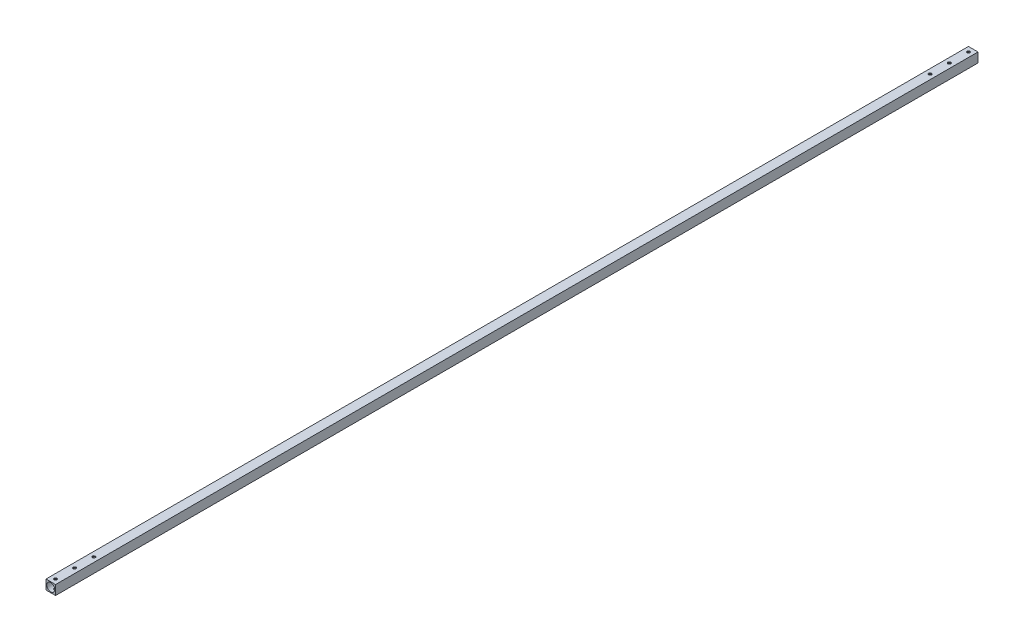
SolidWorks part; units mm, degrees
material "Thornel VCB-20 Carbon Cloth"
ref_plane "Front Plane" through (0, 0, 0) normal (0, 0, 1) x (1, 0, 0)
ref_plane "Top Plane" through (0, 0, 0) normal (0, 1, 0) x (1, 0, 0)
ref_plane "Right Plane" through (0, 0, 0) normal (1, 0, 0) x (0, 0, -1)
sketch "Sketch1" plane through (0, 0, 0) normal (0, 0, 1) x (1, 0, 0)
  line L1 (-5, -5) -> (5, -5)
  line L2 (-5, -5) -> (-5, 5)
  line L3 (-5, 5) -> (5, 5)
  line L4 (5, -5) -> (5, 5)
  line L5 (-5, -5) -> (5, 5) construction
  line L6 (-5, 5) -> (5, -5) construction
  circle A0 centre (0, 0) radius 4.25
  point P0 (0, 0)
  dimension "D3" = 8.5
  dimension "D1" = 10
  dimension "D2" = 10
extrude "Boss-Extrude1" add sketch "Sketch1" along normal blind 964
sketch "Sketch2" plane through (0, 5, 0) normal (0, 1, 0) x (1, 0, 0)
  line L0 (0, 0) -> (0, -5) construction
  line L1 (0, -5) -> (0, -25) construction
  line L2 (0, -25) -> (0, -45) construction
  line L3 (0, -964) -> (0, -959) construction
  line L4 (5, -964) -> (-5, -964) construction
  line L5 (0, -959) -> (0, -939) construction
  line L6 (0, -939) -> (0, -919) construction
  circle A0 centre (0, -5) radius 1.5
  circle A1 centre (0, -25) radius 1.5
  circle A2 centre (0, -45) radius 1.5
  circle A3 centre (0, -959) radius 1.5
  circle A4 centre (0, -939) radius 1.5
  circle A5 centre (0, -919) radius 1.5
  dimension "D3" = 3
  dimension "D4" = 5
  dimension "D6" = 3
  dimension "D1" = 5
  dimension "D2" = 20
  dimension "D5" = 20
extrude "Cut-Extrude1" cut sketch "Sketch2" against normal through all
